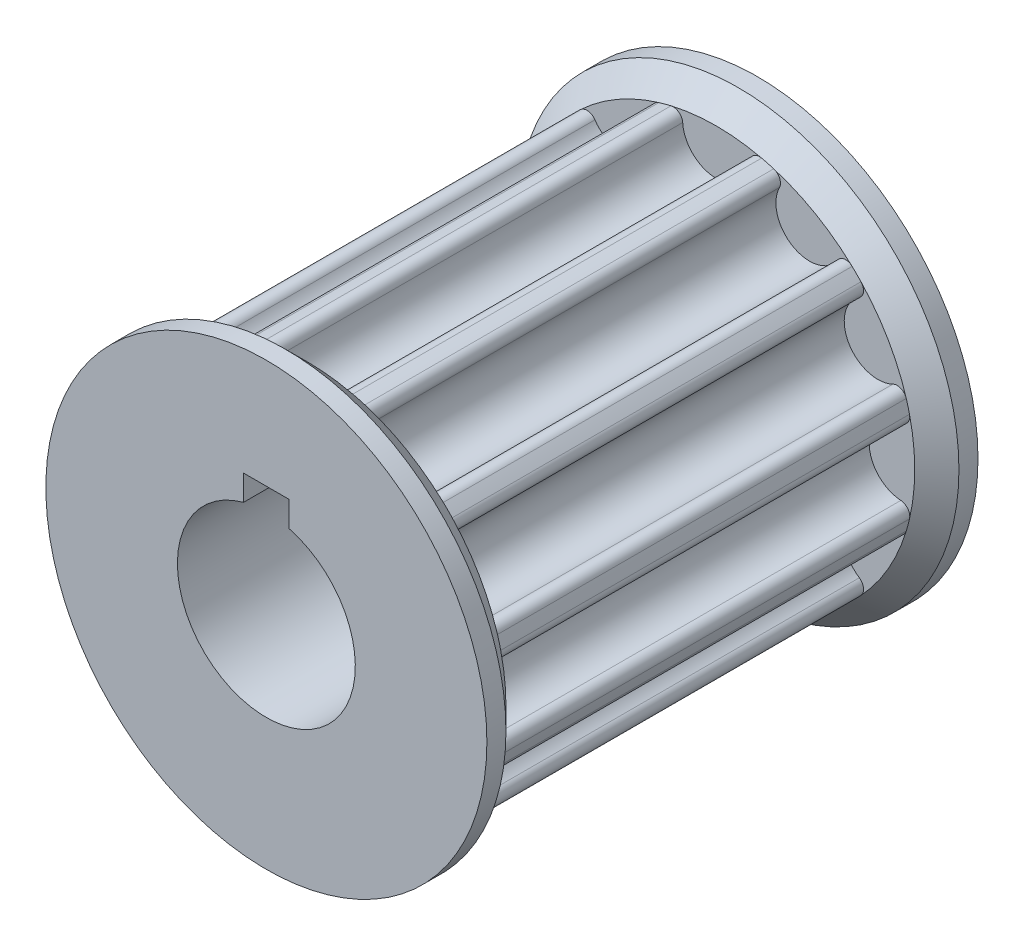
SolidWorks part; units mm, degrees
material "Nailon 6/10"
ref_plane "Alzado" through (0, 0, 0) normal (0, 0, 1) x (1, 0, 0)
ref_plane "Planta" through (0, 0, 0) normal (0, 1, 0) x (1, 0, 0)
ref_plane "Vista lateral" through (0, 0, 0) normal (1, 0, 0) x (0, 0, -1)
sketch "Croquis3" plane through (0, 0, 0) normal (0, 0, 1) x (1, 0, 0)
  line L0 (0, 0) -> (0, 8.98) construction
  line L1 (0, 0) -> (4.49, 7.7769) construction
  circle A0 centre (0, 0) radius 8.98 construction
  circle A1 centre (0, 0) radius 6.92 construction
  circle A2 centre (0, 8.445) radius 1.525 construction
  circle A3 centre (1.9513, 8.3244) radius 0.43 construction
  circle A4 centre (4.2225, 7.3136) radius 1.525 construction
  circle A5 centre (2.4723, 8.1847) radius 0.43 construction
  arc A6 (0, 6.92) -> (1.5221, 8.3509) centre (0, 8.445) ccw
  arc A7 (1.5221, 8.3509) -> (2.0494, 8.743) centre (1.9513, 8.3244) cw
  arc A8 (2.0494, 8.743) -> (2.5967, 8.5964) centre (0, 0) cw
  arc A9 (2.5967, 8.5964) -> (2.8573, 7.9931) centre (2.4723, 8.1847) cw
  arc A10 (2.8573, 7.9931) -> (3.46, 5.9929) centre (4.2225, 7.3136) ccw
  arc A11 (6.471, 5.4936) -> (5.9929, 3.46) centre (7.3136, 4.2225) ccw
  arc A12 (6.547, 6.1463) -> (6.471, 5.4936) centre (6.2335, 5.852) cw
  arc A13 (6.1463, 6.547) -> (6.547, 6.1463) centre (0, 0) cw
  arc A14 (5.4936, 6.471) -> (6.1463, 6.547) centre (5.852, 6.2335) cw
  arc A15 (3.46, 5.9929) -> (5.4936, 6.471) centre (4.2225, 7.3136) ccw
  arc A16 (8.3509, 1.5221) -> (6.92, 0) centre (8.445, 0) ccw
  arc A17 (8.743, 2.0494) -> (8.3509, 1.5221) centre (8.3244, 1.9513) cw
  arc A18 (8.5964, 2.5967) -> (8.743, 2.0494) centre (0, 0) cw
  arc A19 (7.9931, 2.8573) -> (8.5964, 2.5967) centre (8.1847, 2.4723) cw
  arc A20 (5.9929, 3.46) -> (7.9931, 2.8573) centre (7.3136, 4.2225) ccw
  arc A21 (7.9931, -2.8573) -> (5.9929, -3.46) centre (7.3136, -4.2225) ccw
  arc A22 (8.5964, -2.5967) -> (7.9931, -2.8573) centre (8.1847, -2.4723) cw
  arc A23 (8.743, -2.0494) -> (8.5964, -2.5967) centre (0, 0) cw
  arc A24 (8.3509, -1.5221) -> (8.743, -2.0494) centre (8.3244, -1.9513) cw
  arc A25 (6.92, 0) -> (8.3509, -1.5221) centre (8.445, 0) ccw
  arc A26 (5.4936, -6.471) -> (3.46, -5.9929) centre (4.2225, -7.3136) ccw
  arc A27 (6.1463, -6.547) -> (5.4936, -6.471) centre (5.852, -6.2335) cw
  arc A28 (6.547, -6.1463) -> (6.1463, -6.547) centre (0, 0) cw
  arc A29 (6.471, -5.4936) -> (6.547, -6.1463) centre (6.2335, -5.852) cw
  arc A30 (5.9929, -3.46) -> (6.471, -5.4936) centre (7.3136, -4.2225) ccw
  arc A31 (1.5221, -8.3509) -> (0, -6.92) centre (0, -8.445) ccw
  arc A32 (2.0494, -8.743) -> (1.5221, -8.3509) centre (1.9513, -8.3244) cw
  arc A33 (2.5967, -8.5964) -> (2.0494, -8.743) centre (0, 0) cw
  arc A34 (2.8573, -7.9931) -> (2.5967, -8.5964) centre (2.4723, -8.1847) cw
  arc A35 (3.46, -5.9929) -> (2.8573, -7.9931) centre (4.2225, -7.3136) ccw
  arc A36 (-2.8573, -7.9931) -> (-3.46, -5.9929) centre (-4.2225, -7.3136) ccw
  arc A37 (-2.5967, -8.5964) -> (-2.8573, -7.9931) centre (-2.4723, -8.1847) cw
  arc A38 (-2.0494, -8.743) -> (-2.5967, -8.5964) centre (0, 0) cw
  arc A39 (-1.5221, -8.3509) -> (-2.0494, -8.743) centre (-1.9513, -8.3244) cw
  arc A40 (0, -6.92) -> (-1.5221, -8.3509) centre (0, -8.445) ccw
  arc A41 (-6.471, -5.4936) -> (-5.9929, -3.46) centre (-7.3136, -4.2225) ccw
  arc A42 (-6.547, -6.1463) -> (-6.471, -5.4936) centre (-6.2335, -5.852) cw
  arc A43 (-6.1463, -6.547) -> (-6.547, -6.1463) centre (0, 0) cw
  arc A44 (-5.4936, -6.471) -> (-6.1463, -6.547) centre (-5.852, -6.2335) cw
  arc A45 (-3.46, -5.9929) -> (-5.4936, -6.471) centre (-4.2225, -7.3136) ccw
  arc A46 (-8.3509, -1.5221) -> (-6.92, 0) centre (-8.445, 0) ccw
  arc A47 (-8.743, -2.0494) -> (-8.3509, -1.5221) centre (-8.3244, -1.9513) cw
  arc A48 (-8.5964, -2.5967) -> (-8.743, -2.0494) centre (0, 0) cw
  arc A49 (-7.9931, -2.8573) -> (-8.5964, -2.5967) centre (-8.1847, -2.4723) cw
  arc A50 (-5.9929, -3.46) -> (-7.9931, -2.8573) centre (-7.3136, -4.2225) ccw
  arc A51 (-7.9931, 2.8573) -> (-5.9929, 3.46) centre (-7.3136, 4.2225) ccw
  arc A52 (-8.5964, 2.5967) -> (-7.9931, 2.8573) centre (-8.1847, 2.4723) cw
  arc A53 (-8.743, 2.0494) -> (-8.5964, 2.5967) centre (0, 0) cw
  arc A54 (-8.3509, 1.5221) -> (-8.743, 2.0494) centre (-8.3244, 1.9513) cw
  arc A55 (-6.92, 0) -> (-8.3509, 1.5221) centre (-8.445, 0) ccw
  arc A56 (-5.4936, 6.471) -> (-3.46, 5.9929) centre (-4.2225, 7.3136) ccw
  arc A57 (-6.1463, 6.547) -> (-5.4936, 6.471) centre (-5.852, 6.2335) cw
  arc A58 (-6.547, 6.1463) -> (-6.1463, 6.547) centre (0, 0) cw
  arc A59 (-6.471, 5.4936) -> (-6.547, 6.1463) centre (-6.2335, 5.852) cw
  arc A60 (-5.9929, 3.46) -> (-6.471, 5.4936) centre (-7.3136, 4.2225) ccw
  arc A61 (-1.5221, 8.3509) -> (0, 6.92) centre (0, 8.445) ccw
  arc A62 (-2.0494, 8.743) -> (-1.5221, 8.3509) centre (-1.9513, 8.3244) cw
  arc A63 (-2.5967, 8.5964) -> (-2.0494, 8.743) centre (0, 0) cw
  arc A64 (-2.8573, 7.9931) -> (-2.5967, 8.5964) centre (-2.4723, 8.1847) cw
  arc A65 (-3.46, 5.9929) -> (-2.8573, 7.9931) centre (-4.2225, 7.3136) ccw
  dimension "D1" = 17.96
  dimension "D2" = 13.84
  dimension "D3" = 3.05
  dimension "D4" = 0.86
  dimension "D5" = 30
  dimension "D6" = 12
extrude "Saliente-Extruir1" add sketch "Croquis3" along normal mid plane 18.5 contours A65 A56 A57 A58 A59 A60 A51 A52 A53 A54 A55 A46 A47 A48 A49 A50 A41 A42 A43 A44 A45 A36 A37 A38 A39 A40 A31 A32 A33 A34 A35 A26 A27 A28 A29 A30 A21 A22 A23 A24 A25 A16 A17 A18 A19 A20 A11 A12 A13 A14 A15
sketch "Croquis5" plane through (0, 0, 9.25) normal (0, 0, 1) x (1, 0, 0)
  circle A0 centre (0, 0) radius 8.98
  arc A1 (2.5967, 8.5964) -> (2.0494, 8.743) centre (0, 0) ccw construction
extrude "Saliente-Extruir2" add sketch "Croquis5" along normal blind 1 draft 45 draft outward yes
sketch "Croquis8" plane through (0, 0, 10.25) normal (0, 0, 1) x (1, 0, 0)
  circle A0 centre (0, 0) radius 9.98 construction
  circle A1 centre (0, 0) radius 9.98
extrude "Saliente-Extruir3" add sketch "Croquis8" along normal blind 0.8625
mirror "Simetría1" about plane through (0, 0, 0) normal (0, 0, 1) of "Saliente-Extruir3", "Saliente-Extruir2"
sketch "Croquis6" plane through (0, 0, 11.1125) normal (0, 0, 1) x (1, 0, 0)
  line L2 (-1.035, 3.8897) -> (-1.035, 5.04)
  line L3 (-1.035, 5.04) -> (1.035, 5.04)
  line L4 (1.035, 3.8897) -> (1.035, 5.04)
  arc A0 (-1.035, 3.8897) -> (1.035, 3.8897) centre (0, 0) ccw
  point P8 (1.035, 4.4648)
  point P9 (0, 5.04)
  dimension "D1" = 8.05
  dimension "D2" = 2.07
  dimension "D3" = 5.04
extrude "Cortar-Extruir1" cut sketch "Croquis6" against normal through all
equation "\"X\"= 17.96"
equation "\"N\"= 12"
equation "\"D1@Croquis3\"=\"X\""
equation "\"Y\"= \"X\" - 2 * 2.06"
equation "\"A\"= 360 / \"N\""
equation "\"D2@Croquis3\"=\"Y\""
equation "\"D5@Croquis3\"=\"A\""
equation "\"D6@Croquis3\"=\"N\""
